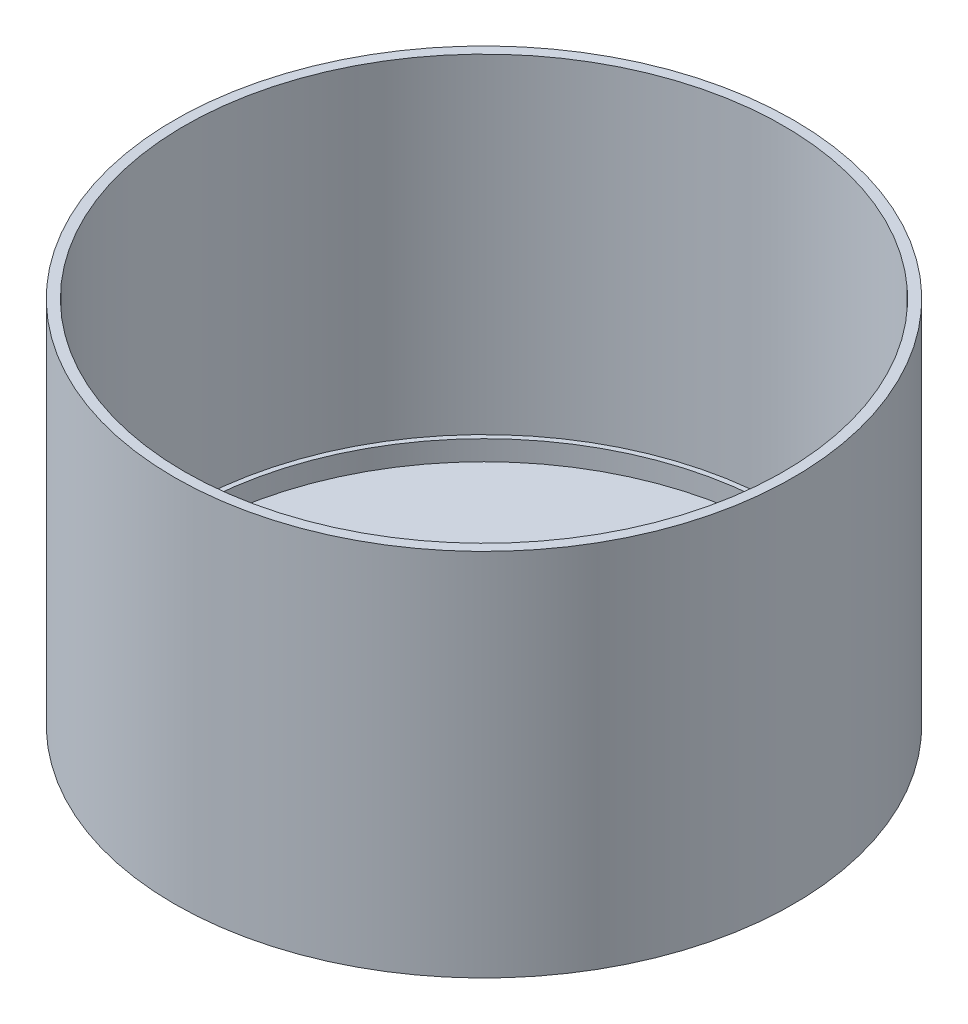
SolidWorks part; units mm, degrees
ref_plane "Alzado" through (0, 0, 0) normal (0, 0, 1) x (1, 0, 0)
ref_plane "Planta" through (0, 0, 0) normal (0, 1, 0) x (1, 0, 0)
ref_plane "Vista lateral" through (0, 0, 0) normal (1, 0, 0) x (0, 0, -1)
sketch "Sketch1" plane through (0, 0, 0) normal (0, 1, 0) x (1, 0, 0)
  circle A2 centre (0, 0) radius 30
  circle A3 centre (0, 0) radius 31
  dimension "D1" = 60
  dimension "D2" = 62
extrude "Boss-Extrude1" add sketch "Sketch1" along normal blind 37
sketch "Sketch2" plane through (0, 0, 0) normal (0, 1, 0) x (1, 0, 0)
  circle A0 centre (0, 0) radius 31
extrude "Boss-Extrude2" add sketch "Sketch2" along normal blind 2
sketch "Sketch5" plane through (0, 2, 0) normal (0, 1, 0) x (1, 0, 0)
  circle A0 centre (0, 0) radius 30
  circle A1 centre (0, 0) radius 29.5
  dimension "D1" = 0.5
extrude "Boss-Extrude4" add sketch "Sketch5" along normal blind 2
sketch "Sketch6" plane through (0, 2, 0) normal (0, 1, 0) x (1, 0, 0)
  circle A0 centre (0, 0) radius 4
  dimension "D1" = 8
extrude "Cut-Extrude1" cut sketch "Sketch6" against normal blind 2
